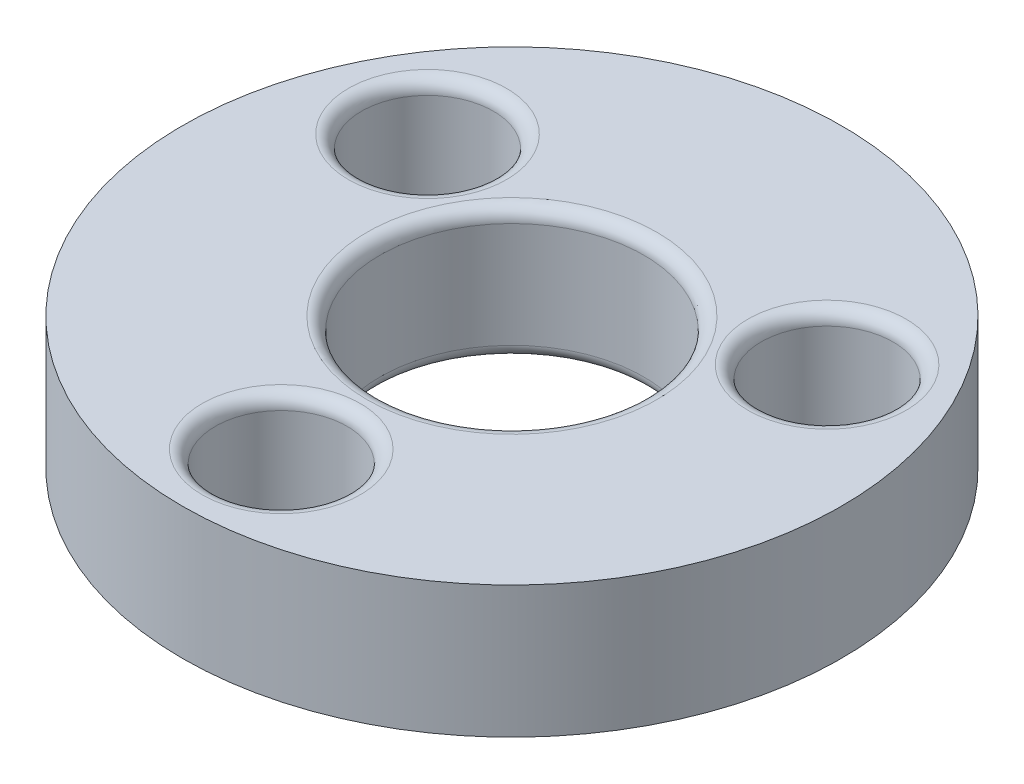
SolidWorks part; units mm, degrees
ref_plane "Front Plane" through (0, 0, 0) normal (0, 0, 1) x (1, 0, 0)
ref_plane "Top Plane" through (0, 0, 0) normal (0, 1, 0) x (1, 0, 0)
ref_plane "Right Plane" through (0, 0, 0) normal (1, 0, 0) x (0, 0, -1)
sketch "Sketch1" plane through (0, 0, 0) normal (0, 1, 0) x (1, 0, 0)
  circle A0 centre (0, 0) radius 25
  circle A1 centre (0, 0) radius 10
  dimension "D1" = 50
  dimension "D2" = 20
extrude "Boss-Extrude1" add sketch "Sketch1" along normal blind 10
sketch "Sketch2" plane through (0, 0, 0) normal (0, -1, 0) x (1, 0, 0)
  circle A0 centre (0, 17.5) radius 5
  circle A1 centre (15.1554, -8.75) radius 5
  circle A2 centre (-15.1554, -8.75) radius 5
  point P10 (0, 0)
  dimension "D1" = 10
  dimension "D2" = 17.5
  dimension "D3" = 3
extrude "Cut-Extrude1" cut sketch "Sketch2" against normal blind 10
fillet "Fillet1" radius 1 8 edges at (-15.1554, 0, -13.75) (-15.1554, 10, -13.75) (15.1554, 0, -13.75) (15.1554, 10, -13.75) (0, 0, 12.5) (0, 10, 12.5) (0, 0, 10) (0, 10, 10)
